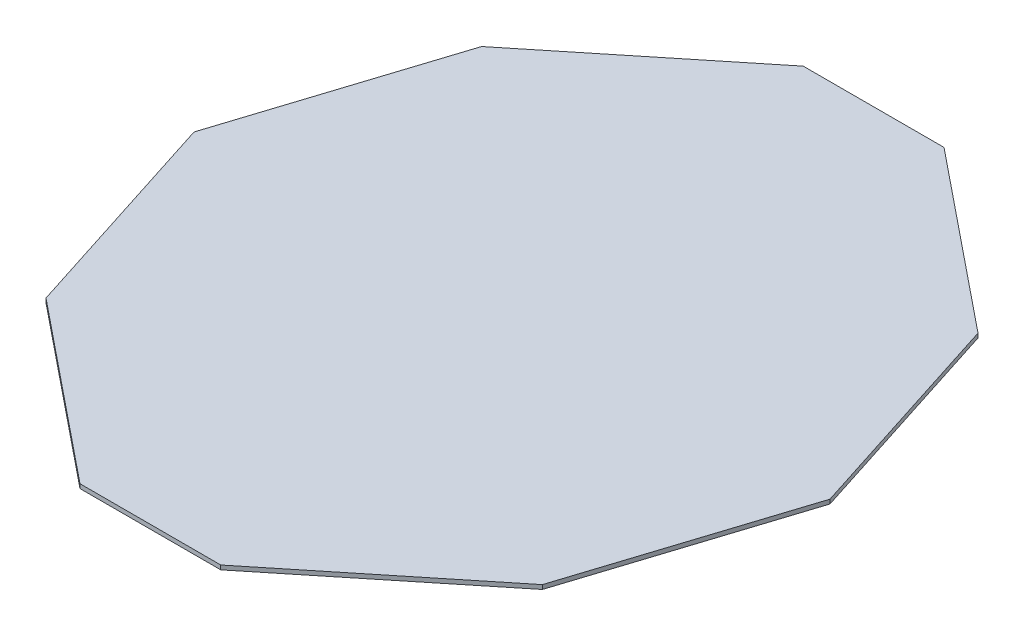
SolidWorks part; units mm, degrees
ref_plane "Front Plane" through (0, 0, 0) normal (0, 0, 1) x (1, 0, 0)
ref_plane "Top Plane" through (0, 0, 0) normal (0, 1, 0) x (1, 0, 0)
ref_plane "Right Plane" through (0, 0, 0) normal (1, 0, 0) x (0, 0, -1)
sketch "Sketch1" plane through (0, 0, 0) normal (0, 1, 0) x (1, 0, 0)
  line L0 (0, 0) -> (8, 0)
  line L1 (8, 0) -> (18.1076, 8.1754)
  line L2 (18.1076, 8.1754) -> (22.0738, 20.5556)
  line L3 (22.0738, 20.5556) -> (18.1076, 32.9358)
  line L4 (18.1076, 32.9358) -> (8, 41.1112)
  line L5 (8, 41.1112) -> (0, 41.1112)
  line L6 (0, 41.1112) -> (-10.1076, 32.9358)
  line L7 (-10.1076, 32.9358) -> (-14.0738, 20.5556)
  line L8 (-14.0738, 20.5556) -> (-10.1076, 8.1754)
  line L9 (-10.1076, 8.1754) -> (0, 0)
  line L10 (-10.1076, 32.9358) -> (18.1076, 32.9358) construction
  line L11 (-14.0738, 20.5556) -> (22.0738, 20.5556) construction
  line L12 (-10.1076, 8.1754) -> (18.1076, 8.1754) construction
  dimension "D1" = 13
  dimension "D2" = 8
extrude "Boss-Extrude1" add sketch "Sketch1" along normal blind 0.24
